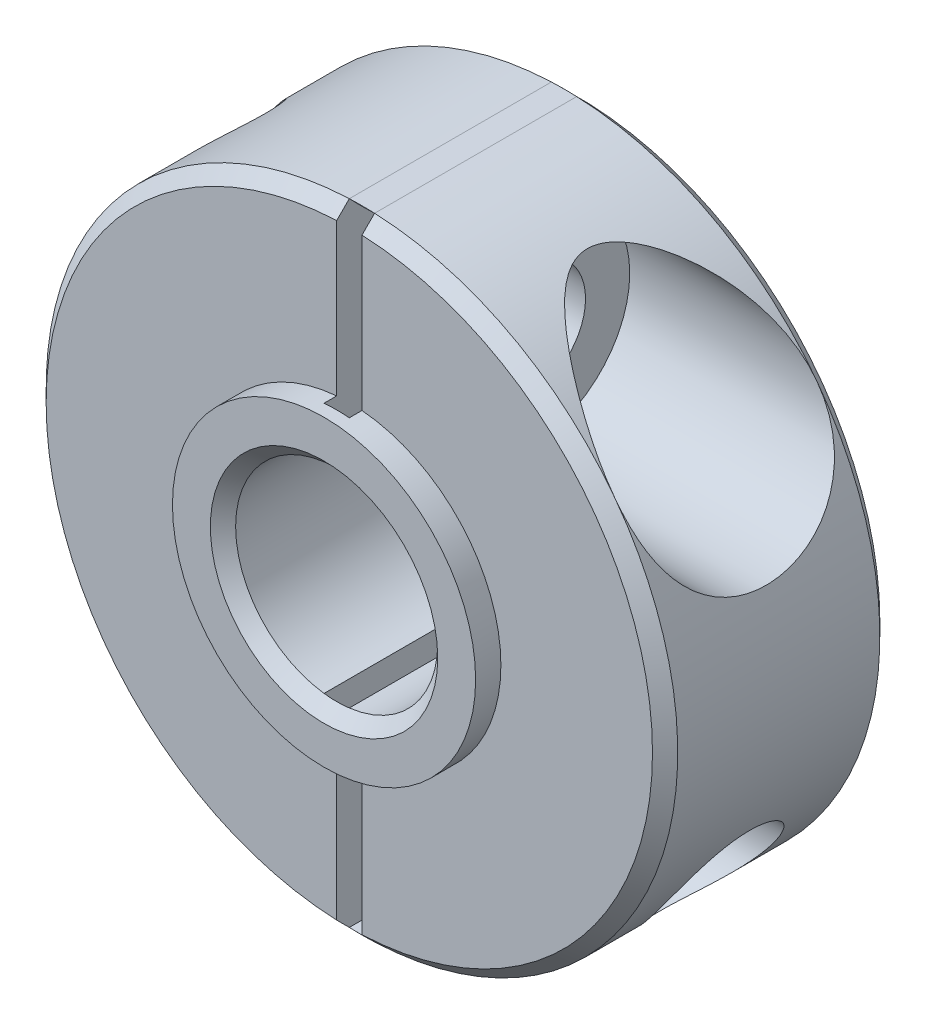
SolidWorks part; units mm, degrees
ref_plane "Alzado" through (0, 0, 0) normal (0, 0, 1) x (1, 0, 0)
ref_plane "Planta" through (0, 0, 0) normal (0, 1, 0) x (1, 0, 0)
ref_plane "Vista lateral" through (0, 0, 0) normal (1, 0, 0) x (0, 0, -1)
sketch "Croquis1" plane through (0, 0, 0) normal (0, 0, 1) x (1, 0, 0)
  circle A0 centre (0, 0) radius 4
  circle A1 centre (0, 0) radius 12.5
  dimension "D1" = 8
  dimension "D2" = 25
extrude "Saliente-Extruir1" add sketch "Croquis1" along normal blind 10
sketch "Croquis2" plane through (0, 0, 10) normal (0, 0, 1) x (1, 0, 0)
  circle A0 centre (0, 0) radius 6
  dimension "D1" = 12
extrude "Cortar-Extruir1" cut sketch "Croquis2" against normal blind 1 flip side to cut
chamfer "Chaflán1" distance 0.5 angle 45 4 edges at (4, 0, 10) (4, 0, 0) (12.5, 0, 0) (12.5, 0, 9)
sketch "Croquis3" plane through (0, 0, 0) normal (0, 0, 1) x (1, 0, 0)
  line L0 (-0.5, 0) -> (0.5, 0) construction
  line L1 (-0.5, 12.49) -> (0.5, 12.49)
  line L2 (-0.5, 12.49) -> (-0.5, -12.49)
  line L3 (-0.5, -12.49) -> (0.5, -12.49)
  line L4 (0.5, 12.49) -> (0.5, -12.49)
  circle A0 centre (0, 0) radius 12.5 construction
  dimension "D1" = 1
extrude "Cortar-Extruir2" cut sketch "Croquis3" along normal blind 9.5
ref_plane "Plano1" through (13, 0, 0) normal (1, 0, 0) x (0, 0, -1)
hole_wizard "Refrentado para tornillo con cabeza troncocónica de M45" positions "Croquis7" profile "Croquis8" counterbore size "M4" standard "Iso"
sketch "Croquis7" plane through (13, 0, 0) normal (1, 0, 0) x (0, 0, -1)
  line L0 (-4.5, 12.49) -> (-4.5, 7.49) construction
  line L1 (-8.5, 12.49) -> (-0.5, 12.49) construction
  point P0 (-4.5, 7.49)
  dimension "D1" = 5
sketch "Croquis8" plane through (13, 7.49, 4.5) normal (0, 1, 0) x (0, 0, -1)
  line L0 (0, 0) -> (0, 31.3519)
  line L1 (0, 31.3519) -> (2.25, 30)
  line L2 (2.25, 30) -> (2.25, 10.4)
  line L3 (2.25, 10.4) -> (4, 10.4)
  line L4 (4, 10.4) -> (4, 0)
  line L5 (4, 0) -> (0, 0)
  line L10 (0, 31.3519) -> (-2.25, 30) construction
  line L11 (0, -6.35) -> (0, 107.95) construction
  dimension "Diámetro de taladro" = 4.5
  dimension "Profundidad de taladro" = 30
  dimension "Diámetro de refrentado" = 8
  dimension "Profundidad de refrentado" = 10.4
  dimension "Ángulo de perforador" = 118
ref_axis "Eje1" through (0, 0, 9.5) along (0, 0, -1)
pattern_circular "MatrizC1" count 2 over 180 about axis through (0, 0, 9.5) along (0, 0, -1) of "Refrentado para tornillo con cabeza troncocónica de M45"
